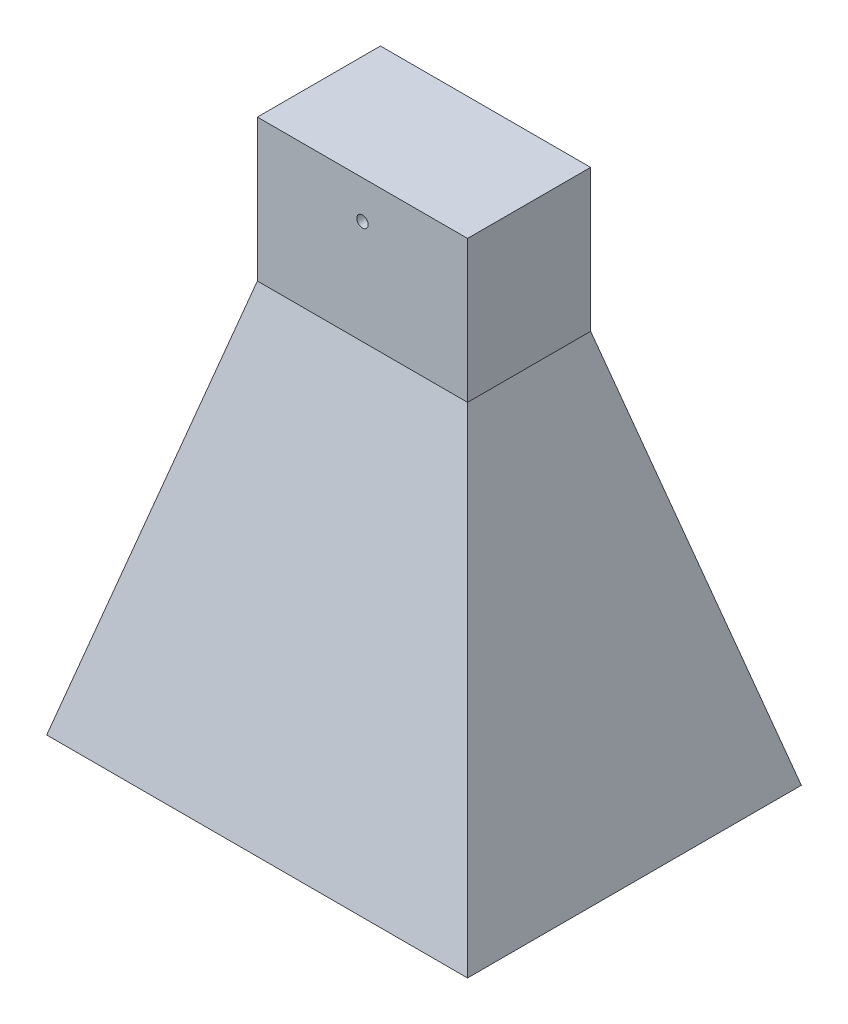
SolidWorks part; units mm, degrees
ref_plane "Front Plane" through (0, 0, 0) normal (0, 0, 1) x (1, 0, 0)
ref_plane "Top Plane" through (0, 0, 0) normal (0, 1, 0) x (1, 0, 0)
ref_plane "Right Plane" through (0, 0, 0) normal (1, 0, 0) x (0, 0, -1)
sketch "Sketch1" plane through (0, 0, 0) normal (0, 1, 0) x (1, 0, 0)
  line L1 (0, 0) -> (744, 0)
  line L2 (0, 0) -> (0, 590)
  line L3 (0, 590) -> (744, 590)
  line L4 (744, 0) -> (744, 590)
  point P6 (0, 0)
  dimension "D1" = 744
  dimension "D2" = 590
extrude "Boss-Extrude1" add sketch "Sketch1" along normal blind 695 draft 15 contours L2 L1 L4 L3
sketch "Sketch6" plane through (0, 0, 0) normal (0, -1, 0) x (1, 0, 0)
  line L8 (5, -585) -> (739, -585)
  line L9 (739, -585) -> (739, -5)
  line L10 (739, -5) -> (5, -5)
  line L11 (5, -5) -> (5, -585)
  line L12 (5, -585) -> (739, -585)
  line L13 (739, -585) -> (739, -5)
  line L14 (739, -5) -> (5, -5)
  line L15 (5, -5) -> (5, -585)
  dimension "D1" = 5
extrude "Cut-Extrude3" cut sketch "Sketch6" against normal blind 784 draft 15
ref_plane "Plane3" through (0, 695, 0) normal (0, 1, 0) x (1, 0, 0)
sketch "Sketch7" plane through (0, 695, 0) normal (0, 1, 0) x (1, 0, 0)
  line L16 (557.7753, 403.7753) -> (186.2247, 403.7753)
  line L17 (186.2247, 403.7753) -> (186.2247, 186.2247)
  line L18 (186.2247, 186.2247) -> (557.7753, 186.2247)
  line L19 (557.7753, 186.2247) -> (557.7753, 403.7753)
  line L20 (557.7753, 403.7753) -> (186.2247, 403.7753)
  line L21 (186.2247, 403.7753) -> (186.2247, 186.2247)
  line L22 (186.2247, 186.2247) -> (557.7753, 186.2247)
  line L23 (557.7753, 186.2247) -> (557.7753, 403.7753)
  dimension "D1" = 0
extrude "Boss-Extrude2" add sketch "Sketch7" along normal blind 251
sketch "Sketch8" plane through (0, 0, -186.2247) normal (0, 0, 1) x (1, 0, 0)
  line L0 (186.2247, 946) -> (557.7753, 946) construction
  line L1 (186.2247, 946) -> (186.2247, 695) construction
  circle A0 centre (372, 879) radius 10
  point P4 (0, 0)
  point P5 (0, 0)
  point P6 (0, 0)
  dimension "D1" = 67
  dimension "D2" = 185.7753
extrude "Cut-Extrude4" cut sketch "Sketch8" against normal blind 100
